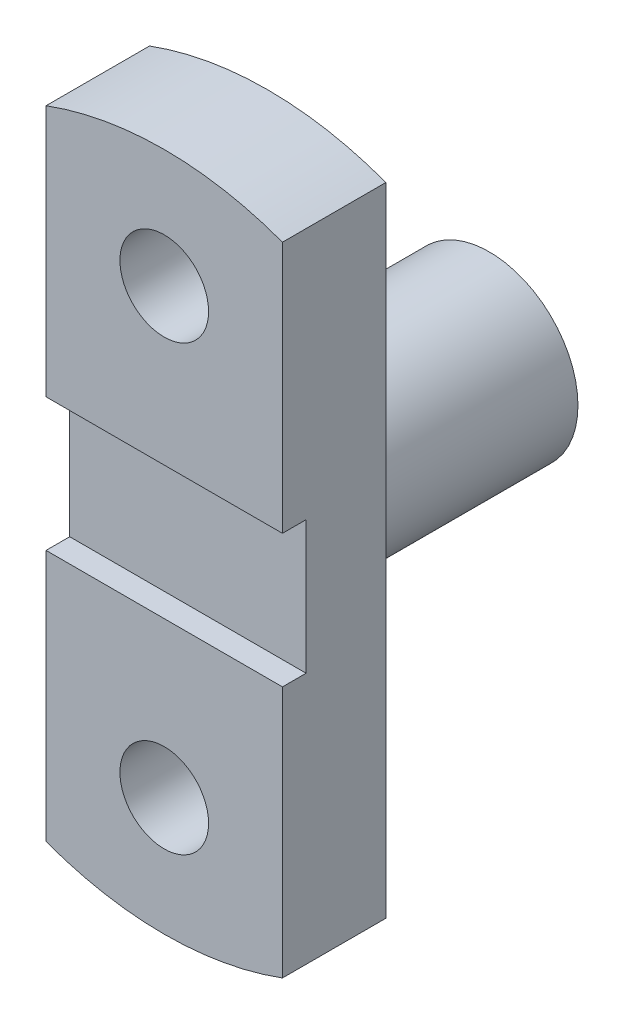
SolidWorks part; units mm, degrees
ref_plane "Front Plane" through (0, 0, 0) normal (0, 0, 1) x (1, 0, 0)
ref_plane "Top Plane" through (0, 0, 0) normal (0, 1, 0) x (1, 0, 0)
ref_plane "Right Plane" through (0, 0, 0) normal (1, 0, 0) x (0, 0, -1)
sketch "Sketch1" plane through (0, 0, 0) normal (0, 0, 1) x (1, 0, 0)
  line L0 (0, 0) -> (0, 147.8361) construction
  line L1 (-40, 107.8193) -> (-40, -107.8193)
  line L2 (40, 107.8193) -> (40, -107.8193)
  arc A0 (-40, -107.8193) -> (40, -107.8193) centre (0, 0) ccw
  arc A1 (40, 107.8193) -> (-40, 107.8193) centre (0, 0) ccw
  circle A2 centre (0, 75) radius 15
  circle A3 centre (0, -75) radius 15
  dimension "D1" = 230
  dimension "D5" = 30
  dimension "D6" = 30
  dimension "D2" = 40
  dimension "D3" = 75
  dimension "D4" = 75
extrude "Boss-Extrude1" add sketch "Sketch1" along normal blind 35
sketch "Sketch2" plane through (40, 0, 0) normal (1, 0, 0) x (0, 0, -1)
  line L0 (-35, -107.8193) -> (-35, 107.8193) construction
  line L1 (-35, 22.5) -> (-27, 22.5)
  line L2 (-35, 22.5) -> (-35, -22.5)
  line L3 (-35, -22.5) -> (-27, -22.5)
  line L4 (-27, 22.5) -> (-27, -22.5)
  dimension "D1" = 45
  dimension "D2" = 22.5
  dimension "D3" = 8
extrude "Cut-Extrude1" cut sketch "Sketch2" against normal blind 216
sketch "Sketch3" plane through (0, 0, 0) normal (0, 0, -1) x (-1, 0, 0)
  circle A0 centre (0, 0) radius 30
  dimension "D1" = 60
extrude "Boss-Extrude2" add sketch "Sketch3" along normal blind 75
